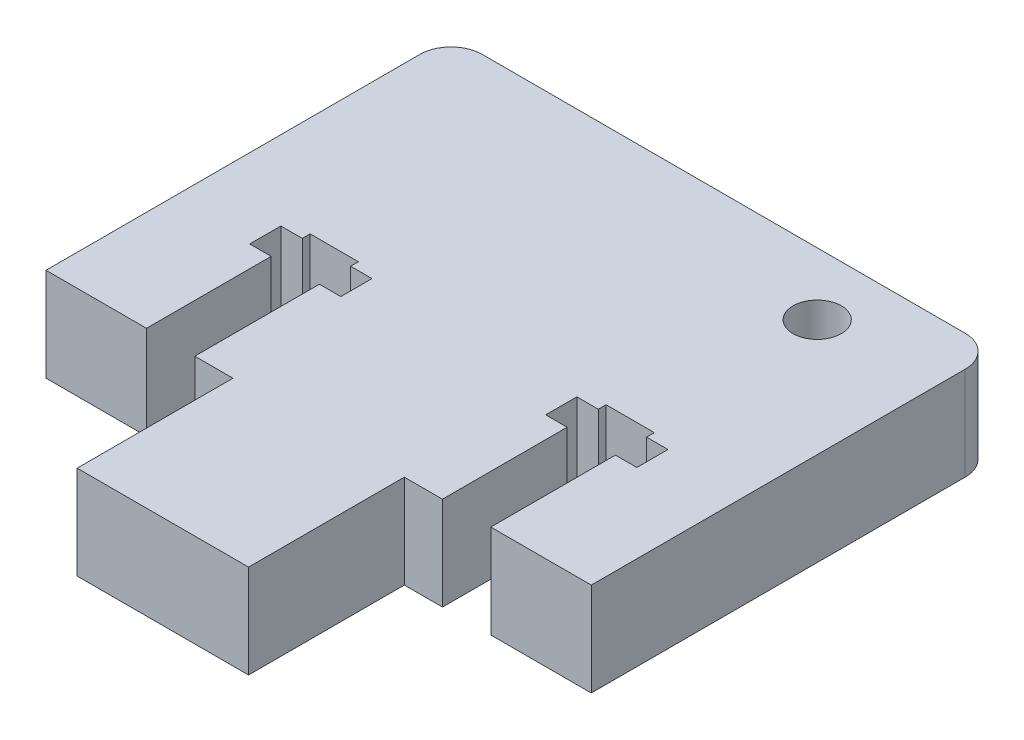
SolidWorks part; units mm, degrees
ref_plane "Płaszczyzna przednia" through (0, 0, 0) normal (0, 0, 1) x (1, 0, 0)
ref_plane "Płaszczyzna górna" through (0, 0, 0) normal (0, 1, 0) x (1, 0, 0)
ref_plane "Płaszczyzna prawa" through (0, 0, 0) normal (1, 0, 0) x (0, 0, -1)
sketch "Szkic1" plane through (0, 0, 0) normal (0, 0, 1) x (1, 0, 0)
  line L0 (74.7241, -88.0624) -> (109.7241, -88.0624)
  line L1 (74.7241, -88.0624) -> (74.7241, -82.0624)
  line L2 (109.7241, -88.0624) -> (109.7241, -82.0624)
  line L3 (74.7241, -82.0624) -> (109.7241, -82.0624)
  dimension "D1" = 6
  dimension "D2" = 35
extrude "Dodanie-wyciągnięcie1" add sketch "Szkic1" along normal blind 20 and the other way blind 6
sketch "Szkic3" plane through (0, -88.0624, 0) normal (0, -1, 0) x (1, 0, 0)
  line L0 (74.7241, 20) -> (109.7241, 20) construction
  line L1 (103.2741, 20) -> (100.1741, 20)
  line L2 (103.2741, 20) -> (103.2741, 12)
  line L3 (103.2741, 9.5) -> (100.1741, 9.5)
  line L4 (100.1741, 20) -> (100.1741, 12)
  line L5 (103.2741, 10) -> (103.2741, 9.5)
  line L6 (104.6491, 10) -> (103.2741, 10)
  line L7 (104.6491, 10) -> (104.6491, 12)
  line L8 (104.6491, 12) -> (103.2741, 12)
  line L9 (98.7991, 10) -> (98.7991, 12)
  line L10 (100.1741, 10) -> (98.7991, 10)
  line L11 (100.1741, 10) -> (100.1741, 9.5)
  line L12 (100.1741, 12) -> (98.7991, 12)
  line L13 (109.7241, -6) -> (109.7241, 20) construction
  point P14 (101.7241, 20)
  dimension "D1" = 10.5
  dimension "D2" = 5.85
  dimension "D3" = 0.5
  dimension "D4" = 1.375
  dimension "D5" = 2
  dimension "D6" = 3.1
  dimension "D7" = 8
extrude "Wytnij-wyciągnięcie1" cut sketch "Szkic3" against normal through all
sketch "Szkic4" plane through (0, -88.0624, 0) normal (0, -1, 0) x (1, 0, 0)
  line L0 (109.7241, -6) -> (109.7241, 20) construction
  line L1 (74.7241, -6) -> (109.7241, -6) construction
  circle A0 centre (102.2241, -2) radius 1.55
  dimension "D1" = 3.1
  dimension "D2" = 7.5
  dimension "D3" = 4
extrude "Wytnij-wyciągnięcie2" cut sketch "Szkic4" against normal blind 6
sketch "Szkic5" plane through (0, 0, 20) normal (0, 0, 1) x (1, 0, 0)
  line L0 (92.2241, -92.139) -> (92.2241, -66.3169) construction
  line L3 (109.7241, -88.0624) -> (109.7241, -82.0624) construction
  dimension "D1" = 17.5
sketch "Szkic6" plane through (0, 0, 20) normal (0, 0, 1) x (1, 0, 0)
  line L0 (97.7241, -88.0624) -> (86.7241, -88.0624)
  line L1 (97.7241, -88.0624) -> (97.7241, -82.0624)
  line L2 (86.7241, -88.0624) -> (86.7241, -82.0624)
  line L3 (97.7241, -82.0624) -> (86.7241, -82.0624)
  line L4 (74.7241, -88.0624) -> (100.1741, -88.0624) construction
  line L6 (109.7241, -88.0624) -> (109.7241, -82.0624) construction
  line L8 (74.7241, -82.0624) -> (74.7241, -88.0624) construction
  dimension "D1" = 12
  dimension "D2" = 12
  dimension "D3" = 6
extrude "Dodanie-wyciągnięcie2" add sketch "Szkic6" along normal blind 10
pattern_linear "Szyk liniowy1" count 2 spacing 19 along (-1, 0, 0) of "Wytnij-wyciągnięcie1"
sketch "Szkic7" plane through (0, -88.0624, 0) normal (0, -1, 0) x (1, 0, 0)
  line L0 (109.7241, -4) -> (109.7241, -6)
  line L2 (109.7241, -6) -> (107.7241, -6)
  line L4 (76.7241, -6) -> (74.7241, -6)
  line L5 (74.7241, -6) -> (74.7241, -4)
  arc A0 (74.7241, -4) -> (76.7241, -6) centre (76.7241, -4) ccw
  arc A1 (109.7241, -4) -> (107.7241, -6) centre (107.7241, -4) cw
  point P12 (74.7241, -6)
  point P15 (109.7241, -6)
  dimension "D1" = 2
extrude "Wytnij-wyciągnięcie3" cut sketch "Szkic7" against normal blind 6
equation "\"tolerancja_wpusy\"=0.2"
equation "\"dlugosc_wpustu_duzy\"=20"
equation "\"srednica_otworu_M3\"=3.1"
equation "\"szerokosc_nogi_T\"=3.1"
equation "\"dlugosc_T_30\"=11"
equation "\"grubosc_na_nakretke_kwadrat\"=2"
equation "\"szerokosc_na_nakretke_kwadrat\"=5.85"
equation "\"wyokosc_nadstawki_T\"=0.5"
equation "\"dlugosc_T_20_6\"=14"
equation "\"D2@Szkic3\"=\"szerokosc_na_nakretke_kwadrat\""
equation "\"D3@Szkic3\"=\"wyokosc_nadstawki_T\""
equation "\"D4@Szkic3\"=(\"szerokosc_na_nakretke_kwadrat\"-\"szerokosc_nogi_T\")/2"
equation "\"D5@Szkic3\"=\"grubosc_na_nakretke_kwadrat\""
equation "\"D6@Szkic3\"=\"szerokosc_nogi_T\""
equation "\"D1@Szkic4\"=\"srednica_otworu_M3\""
